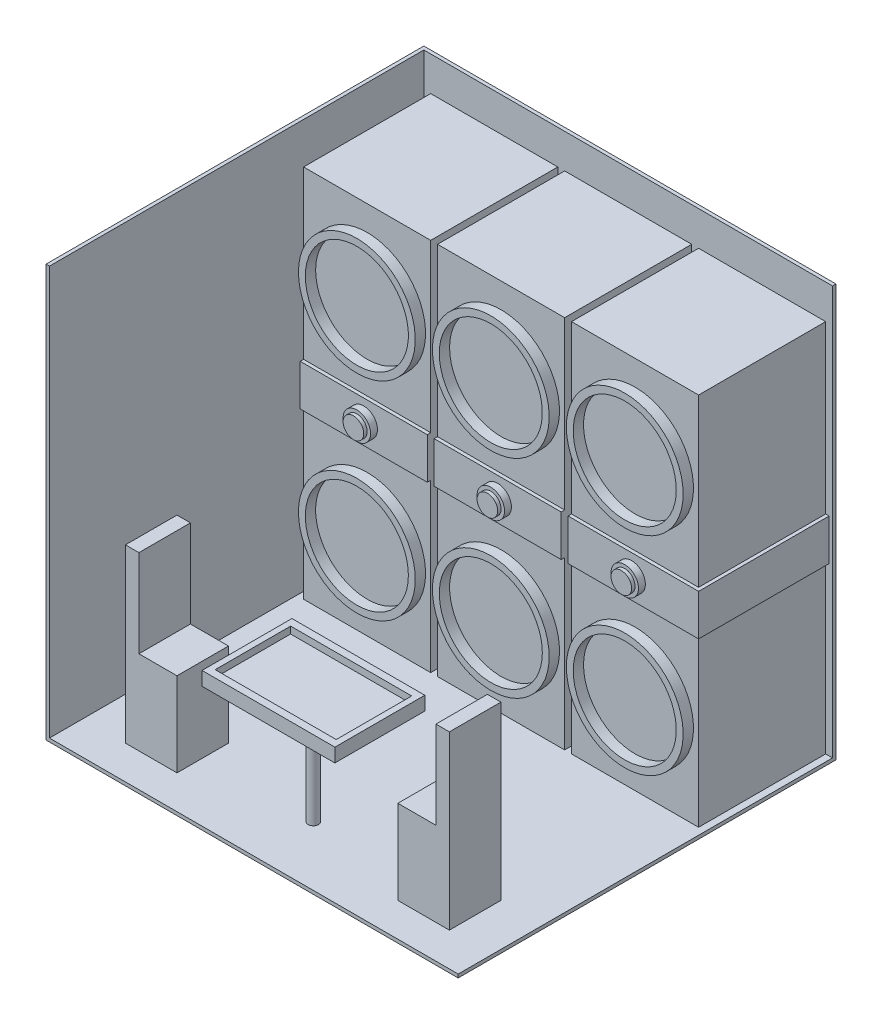
SolidWorks part; units mm, degrees
ref_plane "정면" through (0, 0, 0) normal (0, 0, 1) x (1, 0, 0)
ref_plane "윗면" through (0, 0, 0) normal (0, 1, 0) x (1, 0, 0)
ref_plane "우측면" through (0, 0, 0) normal (1, 0, 0) x (0, 0, -1)
sketch "스케치1" plane through (0, 0, 0) normal (0, 1, 0) x (1, 0, 0)
  line L1 (-60, 55) -> (60, 55)
  line L2 (-60, 55) -> (-60, -55)
  line L3 (-60, -55) -> (60, -55)
  line L4 (60, 55) -> (60, -55)
  line L5 (-60, 55) -> (60, -55) construction
  line L6 (-60, -55) -> (60, 55) construction
  point P0 (0, 0)
  dimension "D1" = 120
  dimension "D2" = 110
extrude "보스-돌출1" add sketch "스케치1" along normal blind 120
sketch "스케치2" plane through (0, 0, 55) normal (0, 0, 1) x (1, 0, 0)
  line L1 (60, 120) -> (-59, 120)
  line L2 (60, 120) -> (60, 1)
  line L3 (60, 1) -> (-59, 1)
  line L4 (-59, 120) -> (-59, 1)
  dimension "D1" = 119
  dimension "D2" = 119
extrude "컷-돌출1" cut sketch "스케치2" against normal blind 109
sketch "스케치22" plane through (0, 1, 0) normal (0, 1, 0) x (1, 0, 0)
  line L0 (60, 17) -> (58, 17)
  line L1 (60, 54) -> (60, -55) construction
  line L2 (58, 17) -> (21, 17)
  line L3 (21, 17) -> (19, 17)
  line L4 (19, 17) -> (-18, 17)
  line L5 (-18, 17) -> (-20, 17)
  line L6 (-20, 17) -> (-57, 17)
  line L7 (-57, 17) -> (-59, 17)
  line L8 (-59, 54) -> (-59, -55) construction
  line L9 (60, 17) -> (60, 54)
  line L11 (-57, 17) -> (-20, 17)
  line L12 (-57, 17) -> (-57, 54)
  line L13 (-57, 54) -> (-20, 54)
  line L14 (-20, 17) -> (-20, 54)
  line L15 (-18, 17) -> (19, 17)
  line L16 (-18, 17) -> (-18, 54)
  line L17 (-18, 54) -> (19, 54)
  line L18 (19, 17) -> (19, 54)
  line L21 (21, 17) -> (58, 17)
  line L22 (21, 17) -> (21, 54)
  line L23 (21, 54) -> (58, 54)
  line L24 (58, 17) -> (58, 54)
  dimension "D1" = 37
  dimension "D2" = 2
  dimension "D3" = 37
  dimension "D4" = 2
  dimension "D5" = 37
  dimension "D6" = 2
  dimension "D7" = 37
  dimension "D8" = 2
sketch "스케치23" plane through (0, 1, 0) normal (0, 1, 0) x (1, 0, 0)
  line L1 (-57, 17) -> (-20, 17)
  line L2 (-57, 17) -> (-57, 54)
  line L3 (-57, 54) -> (-20, 54)
  line L4 (-20, 17) -> (-20, 54)
sketch "스케치46" plane through (0, 1, 0) normal (0, 1, 0) x (1, 0, 0)
  line L1 (-57, 54) -> (-20, 54)
  line L2 (-57, 54) -> (-57, 17)
  line L3 (-57, 17) -> (-20, 17)
  line L4 (-20, 54) -> (-20, 17)
  line L5 (-18, 54) -> (19, 54)
  line L6 (-18, 54) -> (-18, 17)
  line L7 (-18, 17) -> (19, 17)
  line L8 (19, 54) -> (19, 17)
  line L9 (21, 54) -> (58, 54)
  line L10 (21, 54) -> (21, 17)
  line L11 (21, 17) -> (58, 17)
  line L12 (58, 54) -> (58, 17)
sketch "스케치54" plane through (0, 1, 0) normal (0, 1, 0) x (1, 0, 0)
  line L1 (-57, 54) -> (-20, 54)
  line L2 (-57, 54) -> (-57, 17)
  line L3 (-57, 17) -> (-20, 17)
  line L4 (-20, 54) -> (-20, 17)
  line L5 (-18, 54) -> (19, 54)
  line L6 (-18, 54) -> (-18, 17)
  line L7 (-18, 17) -> (19, 17)
  line L8 (19, 54) -> (19, 17)
  line L9 (21, 54) -> (58, 54)
  line L10 (21, 54) -> (21, 17)
  line L11 (21, 17) -> (58, 17)
  line L12 (58, 54) -> (58, 17)
extrude "보스-돌출32" add sketch "스케치54" along normal blind 109
sketch "스케치55" plane through (0, 0, -17) normal (0, 0, 1) x (1, 0, 0)
  line L0 (-57, 55.5) -> (-20, 55.5) construction
  line L1 (-57, 110) -> (-57, 1) construction
  line L2 (-20, 110) -> (-20, 1) construction
  line L3 (-18, 55.5) -> (19, 55.5) construction
  line L4 (-18, 110) -> (-18, 1) construction
  line L5 (19, 110) -> (19, 1) construction
  line L6 (21, 55.5) -> (58, 55.5) construction
  line L7 (21, 110) -> (21, 1) construction
  line L8 (58, 110) -> (58, 1) construction
  line L9 (21, 110) -> (21, 1) construction
  line L10 (-57, 61.5) -> (-20, 61.5)
  line L11 (-57, 61.5) -> (-57, 49.5)
  line L12 (-57, 49.5) -> (-20, 49.5)
  line L13 (-20, 61.5) -> (-20, 49.5)
  line L14 (-57, 61.5) -> (-20, 49.5) construction
  line L15 (-57, 49.5) -> (-20, 61.5) construction
  line L16 (19, 61.5) -> (-18, 61.5)
  line L17 (19, 61.5) -> (19, 49.5)
  line L18 (19, 49.5) -> (-18, 49.5)
  line L19 (-18, 61.5) -> (-18, 49.5)
  line L20 (19, 61.5) -> (-18, 49.5) construction
  line L21 (19, 49.5) -> (-18, 61.5) construction
  line L22 (58, 61.5) -> (21, 61.5)
  line L23 (58, 61.5) -> (58, 49.5)
  line L24 (58, 49.5) -> (21, 49.5)
  line L25 (21, 61.5) -> (21, 49.5)
  line L26 (58, 61.5) -> (21, 49.5) construction
  line L27 (58, 49.5) -> (21, 61.5) construction
  point P18 (-38.5, 55.5)
  point P23 (0.5, 55.5)
  point P28 (39.5, 55.5)
  dimension "D1" = 12
extrude "보스-돌출33" add sketch "스케치55" along normal blind 1
sketch "스케치56" plane through (0, 0, -16) normal (0, 0, 1) x (1, 0, 0)
  line L0 (0.5, 110) -> (0.5, 1) construction
  line L1 (-18, 110) -> (19, 110) construction
  line L2 (-18, 1) -> (19, 1) construction
  line L3 (-38.5, 61.5) -> (-38.5, 49.5) construction
  line L4 (-20, 61.5) -> (-57, 61.5) construction
  line L5 (-57, 49.5) -> (-20, 49.5) construction
  line L6 (39.5, 61.5) -> (39.5, 49.5) construction
  circle A0 centre (-38.5, 55.5) radius 4
  circle A1 centre (39.5, 55.5) radius 4
  circle A2 centre (0.5, 55.5) radius 4
  dimension "D1" = 8
  dimension "D2" = 8
  dimension "D3" = 8
extrude "보스-돌출34" add sketch "스케치56" along normal blind 2 contours A0 | A2 | A1
sketch "스케치57" plane through (0, 0, -14) normal (0, 0, 1) x (1, 0, 0)
  circle A0 centre (-38.5, 55.5) radius 3
  circle A1 centre (0.5, 55.5) radius 3
  circle A2 centre (39.5, 55.5) radius 3
  dimension "D1" = 6
  dimension "D2" = 6
  dimension "D3" = 6
extrude "보스-돌출35" add sketch "스케치57" along normal blind 1 contours A1 | A2 | A0
sketch "스케치59" plane through (0, 0, -17) normal (0, 0, 1) x (1, 0, 0)
  line L0 (-38.5, 1) -> (-38.5, 49.5) construction
  line L1 (-57, 1) -> (-20, 1) construction
  line L2 (-57, 49.5) -> (-20, 49.5) construction
  line L3 (0.5, 49.5) -> (0.5, 1) construction
  line L4 (-18, 49.5) -> (19, 49.5) construction
  line L5 (-18, 1) -> (19, 1) construction
  line L6 (-57, 55.5) -> (58, 55.5) construction
  line L7 (-57, 61.5) -> (-57, 49.5) construction
  line L8 (58, 49.5) -> (58, 61.5) construction
  circle A0 centre (-38.5, 25.25) radius 17
  circle A1 centre (-38.5, 25.25) radius 15
  circle A2 centre (39.5, 25.25) radius 15
  circle A3 centre (39.5, 25.25) radius 17
  circle A4 centre (39.5, 85.75) radius 17
  circle A5 centre (39.5, 85.75) radius 15
  circle A6 centre (-38.5, 85.75) radius 17
  circle A7 centre (-38.5, 85.75) radius 15
  circle A8 centre (0.5, 25.25) radius 17
  circle A9 centre (0.5, 25.25) radius 15
  circle A10 centre (0.5, 85.75) radius 17
  circle A11 centre (0.5, 85.75) radius 15
  dimension "D1" = 34
extrude "보스-돌출36" add sketch "스케치59" along normal blind 3
sketch "스케치60" plane through (58, 0, 0) normal (1, 0, 0) x (0, 0, -1)
  line L0 (16, 61.5) -> (54, 61.5)
  line L1 (54, 110) -> (54, 1) construction
  line L2 (16, 61.5) -> (16, 49.5)
  line L3 (16, 49.5) -> (54, 49.5)
  line L4 (54, 49.5) -> (54, 61.5)
extrude "보스-돌출37" add sketch "스케치60" along normal blind 1
sketch "스케치61" plane through (0, 1, 0) normal (0, 1, 0) x (1, 0, 0)
  circle A0 centre (0.5, -37.649) radius 1.5
extrude "보스-돌출38" add sketch "스케치61" along normal blind 31
sketch "스케치62" plane through (0, 32, 0) normal (0, 1, 0) x (1, 0, 0)
  line L1 (-18.8409, -24.5628) -> (19.8409, -24.5628)
  line L2 (-18.8409, -24.5628) -> (-18.8409, -50.7352)
  line L3 (-18.8409, -50.7352) -> (19.8409, -50.7352)
  line L4 (19.8409, -24.5628) -> (19.8409, -50.7352)
  line L5 (-18.8409, -24.5628) -> (19.8409, -50.7352) construction
  line L6 (-18.8409, -50.7352) -> (19.8409, -24.5628) construction
  point P0 (0.5, -37.649)
extrude "보스-돌출39" add sketch "스케치62" along normal blind 4
sketch "스케치63" plane through (0, 36, 0) normal (0, 1, 0) x (1, 0, 0)
  line L0 (0.5, -50.7352) -> (0.5, -24.5502) construction
  line L1 (-18.8409, -50.7352) -> (19.8409, -50.7352) construction
  line L3 (-17.1231, -26.6594) -> (18.1231, -26.6594)
  line L4 (-17.1231, -26.6594) -> (-17.1231, -48.626)
  line L5 (-17.1231, -48.626) -> (18.1231, -48.626)
  line L6 (18.1231, -26.6594) -> (18.1231, -48.626)
  line L7 (-17.1231, -26.6594) -> (18.1231, -48.626) construction
  line L8 (-17.1231, -48.626) -> (18.1231, -26.6594) construction
  point P4 (0.5, -37.6427)
extrude "컷-돌출9" cut sketch "스케치63" against normal blind 2
sketch "스케치65" plane through (0, 1, 0) normal (0, 1, 0) x (1, 0, 0)
  line L0 (0.5, -55) -> (0.5, 54) construction
  line L1 (-59, -55) -> (60, -55) construction
  line L2 (-18, 54) -> (19, 54) construction
  line L3 (-31.6532, -30.2166) -> (-31.6532, -45.2166)
  line L4 (32.6532, -30.2166) -> (47.6532, -30.2166)
  line L5 (32.6532, -30.2166) -> (32.6532, -45.2166)
  line L6 (32.6532, -45.2166) -> (47.6532, -45.2166)
  line L7 (47.6532, -30.2166) -> (47.6532, -45.2166)
  line L8 (32.6532, -30.2166) -> (47.6532, -45.2166) construction
  line L9 (32.6532, -45.2166) -> (47.6532, -30.2166) construction
  line L10 (-31.6532, -30.2166) -> (-46.6532, -45.2166) construction
  line L11 (-31.6532, -45.2166) -> (-46.6532, -30.2166) construction
  line L12 (-31.6532, -30.2166) -> (-46.6532, -30.2166)
  line L13 (-46.6532, -30.2166) -> (-46.6532, -45.2166)
  line L14 (-31.6532, -45.2166) -> (-46.6532, -45.2166)
  point P6 (40.1532, -37.7166)
  point P15 (-39.1532, -37.7166)
  dimension "D1" = 15
  dimension "D2" = 15
extrude "보스-돌출40" add sketch "스케치65" along normal blind 50
sketch "스케치66" plane through (0, 0, 45.2166) normal (0, 0, 1) x (1, 0, 0)
  line L0 (-46.6532, 51) -> (47.6532, 51) construction
  line L1 (0.5, 51) -> (0.5, 1) construction
  line L2 (-18, 1) -> (19, 1) construction
  line L3 (32.6532, 25.491) -> (43.7352, 25.491)
  line L4 (32.6532, 51) -> (32.6532, 1) construction
  line L5 (-31.6532, 25.491) -> (-42.7352, 25.491)
  line L6 (43.7352, 25.491) -> (43.7352, 51)
  line L7 (-42.7352, 25.491) -> (-42.7352, 51)
  line L8 (43.7352, 51) -> (47.6532, 51)
  line L9 (-42.7352, 51) -> (-46.6532, 51)
  line L10 (47.6532, 51) -> (47.6532, 1)
  line L11 (-46.6532, 51) -> (-46.6532, 1)
  line L12 (47.6532, 1) -> (32.6532, 1)
  line L13 (-46.6532, 1) -> (-31.6532, 1)
  line L14 (32.6532, 1) -> (32.6532, 25.491)
  line L15 (-31.6532, 1) -> (-31.6532, 25.491)
  line L16 (-42.7352, 51) -> (-31.6532, 51)
  line L17 (-31.6532, 51) -> (-31.6532, 1) construction
  line L18 (43.7352, 51) -> (32.6532, 51)
  line L19 (-31.6532, 51) -> (-31.6532, 25.491)
  line L20 (32.6532, 51) -> (32.6532, 25.491)
  line M11 (47.6532, 51) -> (32.6532, 51)
  line M12 (32.6532, 51) -> (32.6532, 1)
extrude "컷-돌출10" cut sketch "스케치66" against normal blind 30 contours L19 L16 L7 L5 | L3 L6 M11 M12
